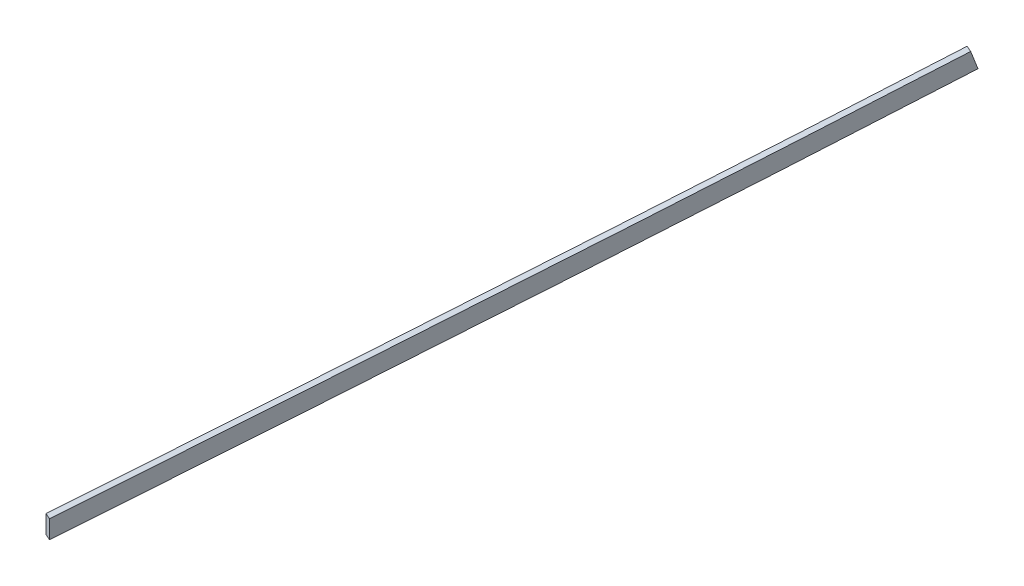
SolidWorks part; units mm, degrees
material "Balsa"
ref_plane "Front Plane" through (0, 0, 0) normal (0, 0, 1) x (1, 0, 0)
ref_plane "Top Plane" through (0, 0, 0) normal (0, 1, 0) x (1, 0, 0)
ref_plane "Right Plane" through (0, 0, 0) normal (1, 0, 0) x (0, 0, -1)
ref_plane "Plane1" through (190.506, 0, 85.0258) normal (-0.9132, 0, -0.4076) x (-0.4076, 0, 0.9132)
sketch "Sketch1" plane through (190.506, 0, 85.0258) normal (-0.9132, 0, -0.4076) x (-0.4076, 0, 0.9132)
  line L0 (-451.1919, -3.4342) -> (-449.1456, 2.5771)
  line L1 (-186.9493, -89.9188) -> (-185.0221, -83.8684)
  spline S0 degree 3 poles (-1924.5071, 1266.5475) (-1551.8093, 415.8575) (-976.6733, 170.855) (-363.3145, -32.8793) (-341.3033, -40.1156) (355.6227, -267.4994) (1045.4218, -441.9535) (1652.3506, -860.7637) knots -6.473611 -6.473611 -6.473611 -6.473611 0.25 0.25 0.5 0.5 8.15982 8.15982 8.15982 8.15982 only from (-451.1919, -3.4342) to (-186.9493, -89.9188)
  spline S1 degree 3 poles (-451.1919, -3.4342) (-429.2578, -10.9009) (-407.2917, -18.2718) (-363.3145, -32.8793) (-341.3033, -40.1156) (-275.2216, -61.6758) (-231.1036, -75.8545) (-186.9493, -89.9188) knots 0 0 0 0 0.25 0.25 0.5 0.5 1 1 1 1
  spline S2 degree 1 poles (-449.1456, 2.5771) (-185.0221, -83.8684) knots 0 0 1 1 construction
  spline S3 degree 3 poles (-449.1456, 2.5771) (-427.2266, -4.8845) (-383.3272, -19.6156) (-317.3233, -41.3144) (-251.2182, -62.72) (-207.0931, -76.8381) (-185.0221, -83.8684) knots 0 0 0 0 0.25 0.5 0.75 1 1 1 1
  dimension "D1" = 6.35
extrude "Boss-Extrude1" add sketch "Sketch1" along normal blind 2.54
sketch "Sketch2" plane through (188.1865, 0, 83.9906) normal (-0.9132, 0, -0.4076) x (-0.4076, 0, 0.9132)
  line L0 (-192.6404, 54.2958) -> (-192.6404, 37.1534)
  line L1 (-192.6404, -76.0715) -> (-192.6404, -93.064)
  line L2 (-192.6404, -81.4405) -> (-192.6404, -88.1054)
  line L3 (-186.9493, -89.9188) -> (-185.0221, -83.8684)
  line L4 (-449.1456, 2.5771) -> (-451.1919, -3.4342)
  line L5 (-186.9493, -89.9188) -> (-185.0221, -83.8684)
  line L8 (-192.6404, -33.6224) -> (-192.6404, -62.4067)
  line L10 (-192.6404, 54.2958) -> (-192.6404, 37.1534)
  line L11 (-192.6404, -33.6224) -> (-192.6404, -62.4067)
  spline S2 degree 3 poles (-2203.2225, 2226.8937) (-1900.2728, 569.4359) (-1156.5956, 230.6182) (-363.3145, -32.8793) (-341.3033, -40.1156) (643.1559, -361.312) (1635.889, -582.2992) (2375.3906, -1551.5439) knots -8.519246 -8.519246 -8.519246 -8.519246 0.25 0.25 0.5 0.5 11.423202 11.423202 11.423202 11.423202 only from (-451.1919, -3.4342) to (-186.9493, -89.9188)
  spline S3 degree 3 poles (2309.8025, -1615.7907) (1750.1247, -621.7156) (712.995, -374.9443) (-317.3233, -41.3144) (-1115.2102, 220.9905) (-1859.0178, 558.5542) (-2350.9283, 2156.5555) knots -10.939553 -10.939553 -10.939553 -10.939553 0.25 0.5 0.75 9.316361 9.316361 9.316361 9.316361 only from (-185.0221, -83.8684) to (-449.1456, 2.5771)
  spline S4 degree 3 poles (-192.6404, -88.1054) (-190.7434, -88.7101) (-188.8464, -89.3146) (-186.9493, -89.9188) knots 0.978518 0.978518 0.978518 0.978518 1 1 1 1
  spline S5 degree 3 poles (-185.0221, -83.8684) (-187.5616, -83.0595) (-190.1011, -82.2502) (-192.6404, -81.4405) knots 0 0 0 0 0.028766 0.028766 0.028766 0.028766
  dimension "D1" = 0
extrude "Cut-Extrude1" cut sketch "Sketch2" against normal through all contours L5 S5 L2 S4
